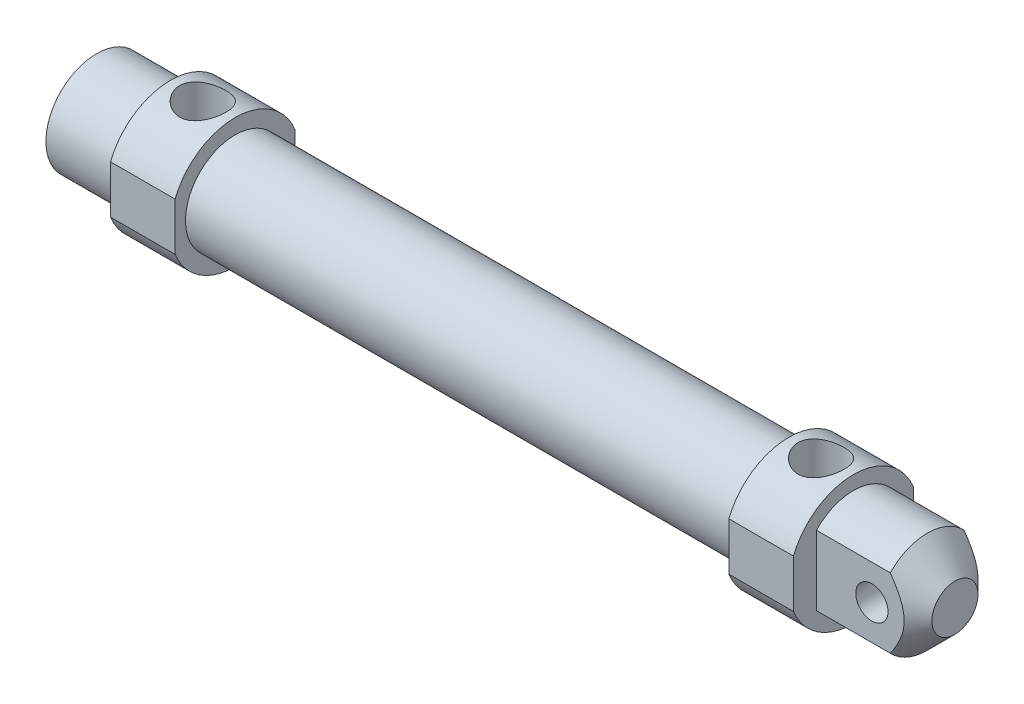
SolidWorks part; units mm, degrees
ref_plane "Front" through (0, 0, 0) normal (0, 0, 1) x (1, 0, 0)
ref_plane "Top" through (0, 0, 0) normal (0, 1, 0) x (1, 0, 0)
ref_plane "Right" through (0, 0, 0) normal (1, 0, 0) x (0, 0, -1)
sketch "ｽｹｯﾁ2" plane through (0, 0, 0) normal (1, 0, 0) x (0, 0, -1)
  circle A0 centre (0, 0) radius 11
  dimension "D1" = 22
extrude "ﾎﾞｽ - 押し出し1" add sketch "ｽｹｯﾁ2" along normal blind 16
sketch "ｽｹｯﾁ4" plane through (16, 0, 0) normal (1, 0, 0) x (0, 0, -1)
  line L1 (-13, 5.1962) -> (13, 5.1962)
  line L2 (-13, 5.1962) -> (-13, -5.1962)
  line L3 (-13, -5.1962) -> (13, -5.1962)
  line L4 (13, 5.1962) -> (13, -5.1962)
  line L5 (0, -5.1962) -> (0, 5.1962) construction
  line L6 (-13, 0) -> (13, 0) construction
  circle A0 centre (0, 0) radius 14
  circle M3 centre (0, 0) radius 11
  dimension "D1" = 28
  dimension "D2" = 26
extrude "ﾎﾞｽ - 押し出し2" add sketch "ｽｹｯﾁ4" along normal blind 14 contours L4 L1 L3 M3 | L3 L1 M3 | L2 L3 L1 M3 | L1 A0 M3 | L1 M3 | L3 M3 | L3 A0 M3
sketch "ｽｹｯﾁ5" plane through (30, 0, 0) normal (1, 0, 0) x (0, 0, -1)
  circle A0 centre (0, 0) radius 10.75
  dimension "D1" = 21.5
extrude "ﾎﾞｽ - 押し出し3" add sketch "ｽｹｯﾁ5" along normal blind 120
sketch "ｽｹｯﾁ6" plane through (150, 0, 0) normal (1, 0, 0) x (0, 0, -1)
  line L1 (-13, -5.1962) -> (13, -5.1962)
  line L2 (-13, -5.1962) -> (-13, 5.1962)
  line L3 (-13, 5.1962) -> (13, 5.1962)
  line L4 (13, -5.1962) -> (13, 5.1962)
  line L5 (0, 5.1962) -> (0, -5.1962) construction
  line L6 (-13, 0) -> (13, 0) construction
  circle A0 centre (0, 0) radius 14
  circle M3 centre (0, 0) radius 10.75
  dimension "D1" = 28
  dimension "D2" = 26
extrude "ﾎﾞｽ - 押し出し4" add sketch "ｽｹｯﾁ6" along normal blind 14 contours L3 M3 | L3 A0 M3 | L3 L1 M3 | L1 L4 L3 M3 | L3 L2 L1 M3 | L1 M3 | L1 A0 M3
sketch "ｽｹｯﾁ7" plane through (0, 0, 0) normal (-1, 0, 0) x (0, 0, 1)
  circle A0 centre (0, 0) radius 8
  dimension "D1" = 16
extrude "ｶｯﾄ - 押し出し1" cut sketch "ｽｹｯﾁ7" against normal blind 3
sketch "ｽｹｯﾁ8" plane through (3, 0, 0) normal (-1, 0, 0) x (0, 0, 1)
  circle A0 centre (0, 0) radius 4
  dimension "D1" = 8
extrude "ｶｯﾄ - 押し出し2" cut sketch "ｽｹｯﾁ8" against normal blind 100
ref_plane "平面1" through (0, 20, 0) normal (0, 1, 0) x (1, 0, 0)
sketch "ｽｹｯﾁ9" plane through (0, 20, 0) normal (0, 1, 0) x (1, 0, 0)
  line L0 (30, -13) -> (30, 13) construction
  line L1 (164, -13) -> (164, 13) construction
  line L2 (164, -13) -> (150, -13) construction
  line L3 (30, -13) -> (16, -13) construction
  circle A0 centre (23, 0) radius 5
  circle A1 centre (157, 0) radius 5
  dimension "D1" = 10
  dimension "D2" = 7
  dimension "10" = 10
  dimension "D3" = 7
  dimension "D4" = 13
  dimension "D5" = 13
extrude "ｶｯﾄ - 押し出し3" cut sketch "ｽｹｯﾁ9" against normal blind 15
sketch "ｽｹｯﾁ10" plane through (164, 0, 0) normal (1, 0, 0) x (0, 0, -1)
  circle A0 centre (0, 0) radius 11
  dimension "D1" = 22
extrude "ﾎﾞｽ - 押し出し5" add sketch "ｽｹｯﾁ10" along normal blind 22
chamfer "面取り1" distance 6 angle 45 1 edges at (186, 0, -11)
sketch "ｽｹｯﾁ11" plane through (186, 0, 0) normal (1, 0, 0) x (0, 0, -1)
  line L1 (-8, -7.5498) -> (8, -7.5498)
  line L2 (-8, -7.5498) -> (-8, 7.5498)
  line L3 (-8, 7.5498) -> (8, 7.5498)
  line L4 (8, -7.5498) -> (8, 7.5498)
  line L5 (0, 7.5498) -> (0, -7.5498) construction
  line L6 (-8, 0) -> (8, 0) construction
  circle A1 centre (0, 0) radius 11
  circle A2 centre (0, 0) radius 11
  dimension "D2" = 16
  dimension "D1" = 0
extrude "ｶｯﾄ - 押し出し4" cut sketch "ｽｹｯﾁ11" against normal blind 22 contours L2 A2 | L4 A2
sketch "ｽｹｯﾁ12" plane through (0, 0, 8) normal (0, 0, 1) x (1, 0, 0)
  line L0 (164, -7.5498) -> (164, 7.5498) construction
  line L1 (164, -7.5498) -> (180, -7.5498) construction
  circle A0 centre (176, 0) radius 3.5
  dimension "D1" = 7
  dimension "D2" = 12
  dimension "D3" = 7.5498
extrude "ｶｯﾄ - 押し出し5" cut sketch "ｽｹｯﾁ12" against normal through all
